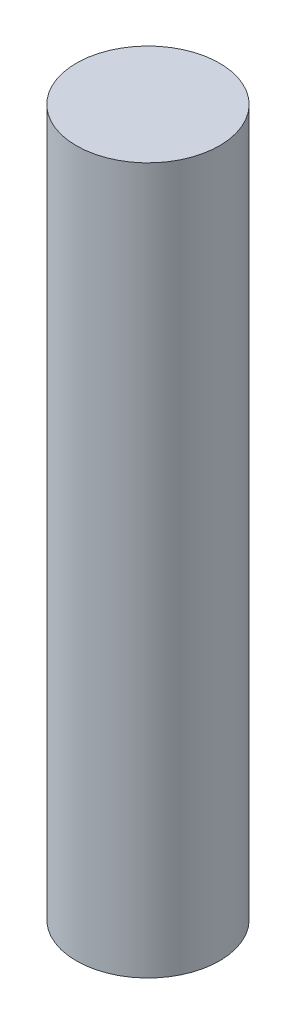
SolidWorks part; units mm, degrees
ref_plane "前视基准面" through (0, 0, 0) normal (0, 0, 1) x (1, 0, 0)
ref_plane "上视基准面" through (0, 0, 0) normal (0, 1, 0) x (1, 0, 0)
ref_plane "右视基准面" through (0, 0, 0) normal (1, 0, 0) x (0, 0, -1)
other "Configuration Table"
sketch "草图1" plane through (0, 0, 0) normal (0, 1, 0) x (1, 0, 0)
  circle A0 centre (0, 0) radius 3.65
  dimension "D1" = 7.3
extrude "凸台-拉伸1" add sketch "草图1" along normal blind 36
